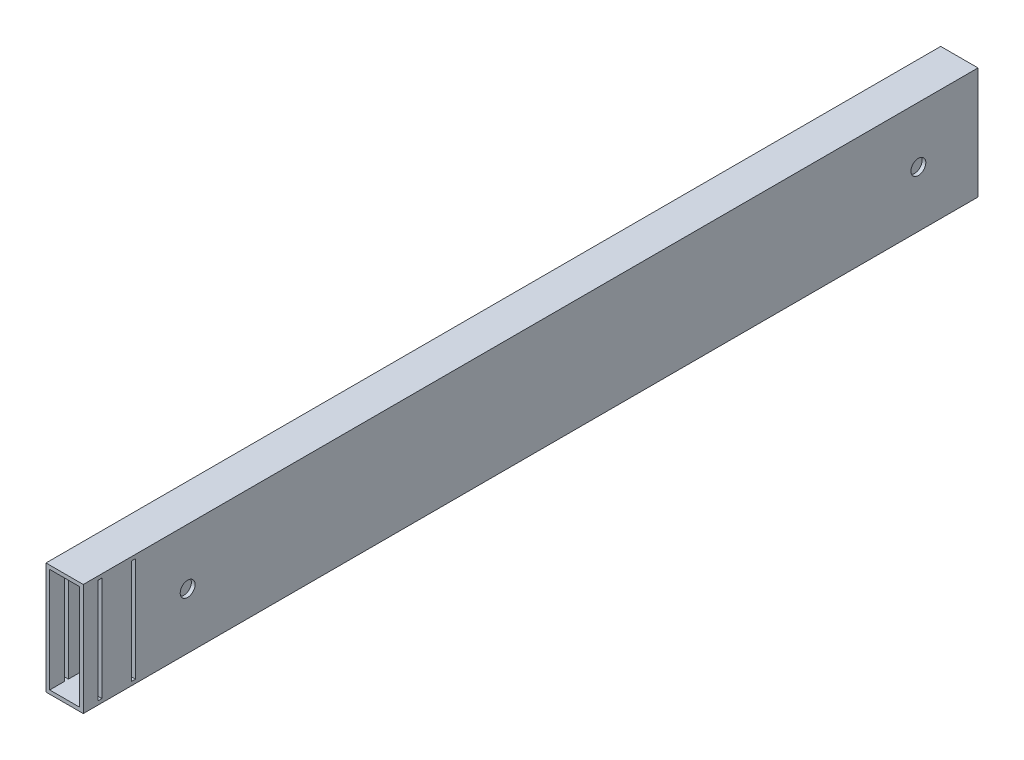
SolidWorks part; units mm, degrees
ref_plane "Front Plane" through (0, 0, 0) normal (0, 0, 1) x (1, 0, 0)
ref_plane "Top Plane" through (0, 0, 0) normal (0, 1, 0) x (1, 0, 0)
ref_plane "Right Plane" through (0, 0, 0) normal (1, 0, 0) x (0, 0, -1)
sketch "Sketch1" plane through (0, 0, 0) normal (0, 1, 0) x (1, 0, 0)
  line L0 (-125, -270) -> (-75, -270)
  line L5 (-125, 250) -> (-125, -250)
  line L7 (-75, -270) -> (-75, 930)
  line L12 (-125, -270) -> (-125, 930)
  line L13 (-125, 930) -> (-75, 930)
  dimension "D1" = 1200
  dimension "D6" = 50
extrude "Boss-Extrude1" add sketch "Sketch1" along normal blind 150 contours L0 L7 L13 L12
sketch "Sketch13" plane through (-75, 0, 0) normal (1, 0, 0) x (0, 0, -1)
  circle A0 centre (-241.899, 15) radius 8
  dimension "D1" = 16
sketch "Sketch16" plane through (0, 0, 270) normal (0, 0, 1) x (1, 0, 0)
  line L0 (-75, 150) -> (-75, 0) construction
  line L4 (-100, 5) -> (-120, 5)
  line L5 (-120, 5) -> (-120, 145)
  line L7 (-125, 150) -> (-75, 150) construction
  line L8 (-100, 5) -> (-80, 5)
  line L9 (-80, 5) -> (-80, 145)
  line L10 (-80, 145) -> (-120, 145)
  dimension "D1" = 5
  dimension "D2" = 140
  dimension "D3" = 5
  dimension "D4" = 40
extrude "Cut-Extrude4" cut sketch "Sketch16" against normal through all
sketch "Sketch18" plane through (-75, 0, 0) normal (1, 0, 0) x (0, 0, -1)
  line L1 (-250, 145) -> (-250, 5)
  line L8 (-270, 150) -> (930, 150) construction
  line L13 (-245, 5) -> (-245, 145)
  line L14 (-270, 0) -> (930, 0) construction
  line L15 (-250, 145) -> (-245, 145)
  line L16 (-250, 5) -> (-245, 5)
  line L17 (-270, 150) -> (-270, 0) construction
  line L18 (930, 150) -> (930, 0) construction
  point P2 (-247.5, 5)
  dimension "D1" = 5
  dimension "D2" = 5
  dimension "D3" = 20
  dimension "D4" = 1175
extrude "Cut-Extrude6" cut sketch "Sketch18" against normal through all
sketch "Sketch19" plane through (-75, 0, 0) normal (1, 0, 0) x (0, 0, -1)
  line L0 (-205, 5) -> (-200, 5)
  line L2 (-205, 5) -> (-205, 145)
  line L3 (-200, 5) -> (-200, 145)
  line L4 (-200, 145) -> (-205, 145)
  line L7 (-270, 150) -> (930, 150) construction
  line L8 (930, 150) -> (930, 0) construction
  dimension "D1" = 50
  dimension "D2" = 5
  dimension "D3" = 5
  dimension "D4" = 1130
extrude "Cut-Extrude7" cut sketch "Sketch19" against normal through all
sketch "Sketch20" plane through (-75, 0, 0) normal (1, 0, 0) x (0, 0, -1)
  line L0 (-270, 150) -> (930, 150) construction
  line L3 (-200, 5) -> (-200, 145) construction
  line L4 (930, 75) -> (850, 75) construction
  line L6 (930, 150) -> (930, 0) construction
  circle A1 centre (-130, 75) radius 10
  circle A3 centre (850, 75) radius 10
  dimension "D1" = 20
  dimension "D2" = 75
  dimension "D3" = 70
  dimension "D4" = 20
  dimension "D5" = 80
extrude "Cut-Extrude8" cut sketch "Sketch20" against normal through all contours A1 | A3
